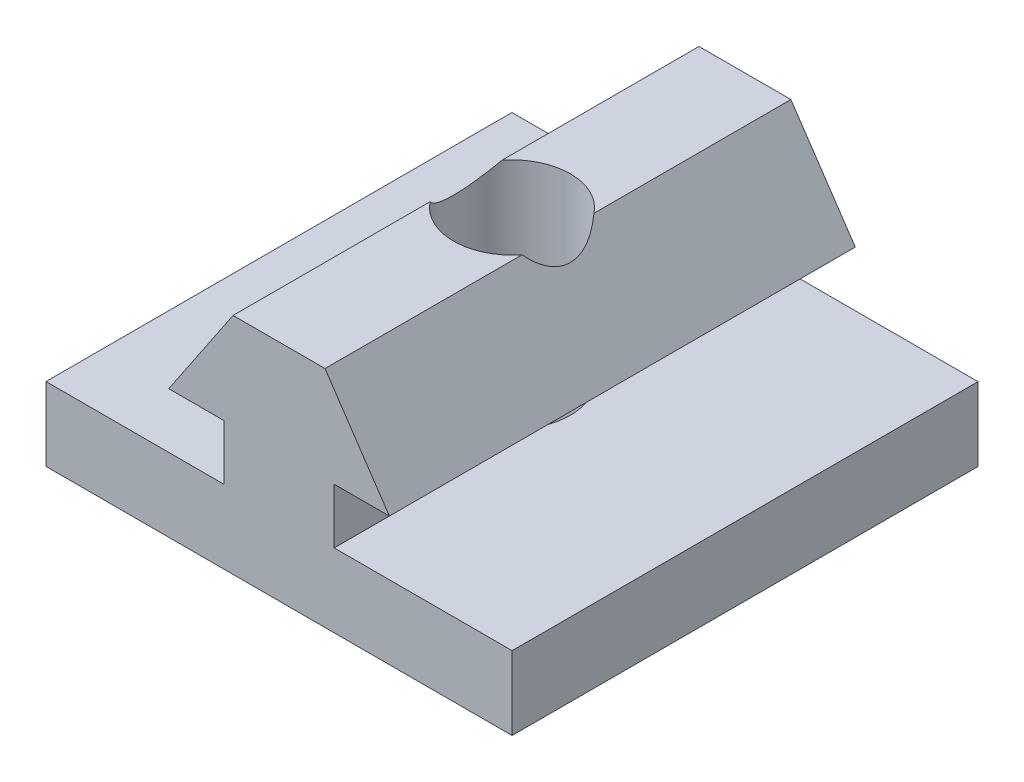
SolidWorks part; units mm, degrees
ref_plane "Front Plane" through (0, 0, 0) normal (0, 0, 1) x (1, 0, 0)
ref_plane "Top Plane" through (0, 0, 0) normal (0, 1, 0) x (1, 0, 0)
ref_plane "Right Plane" through (0, 0, 0) normal (1, 0, 0) x (0, 0, -1)
sketch "Sketch1" plane through (0, 0, 0) normal (0, 0, 1) x (1, 0, 0)
  line L0 (0, 0) -> (0, 27.2727) construction
  line L1 (12.675, 0) -> (-12.675, 0)
  line L2 (-12.675, 0) -> (-12.675, 4)
  line L3 (-12.675, 4) -> (-3, 4)
  line L4 (-3, 4) -> (-3, 7)
  line L5 (-3, 7) -> (-6, 7)
  line L6 (-6, 7) -> (-2.5, 12.2)
  line L7 (-2.5, 12.2) -> (2.5, 12.2)
  line L8 (6, 7) -> (2.5, 12.2)
  line L9 (3, 7) -> (6, 7)
  line L10 (3, 4) -> (3, 7)
  line L11 (12.675, 4) -> (3, 4)
  line L12 (12.675, 0) -> (12.675, 4)
  point P12 (0, 12.2)
  dimension "D1" = 4
  dimension "D2" = 3
  dimension "D3" = 3
  dimension "D4" = 12.2
  dimension "D5" = 6
  dimension "D6" = 5
  dimension "D7" = 25.35
extrude "Boss-Extrude1" add sketch "Sketch1" along normal blind 25.34
sketch "Sketch2" plane through (0, 0, 0) normal (0, -1, 0) x (1, 0, 0)
  line L0 (-12.675, 25.34) -> (12.675, 0) construction
  circle A0 centre (0, 12.67) radius 3.175
  dimension "D1" = 6.35
extrude "Cut-Extrude1" cut sketch "Sketch2" against normal through all
ref_plane "Plane1" through (0, 0, 0) normal (1, 0, 0) x (0, 0, -1)
